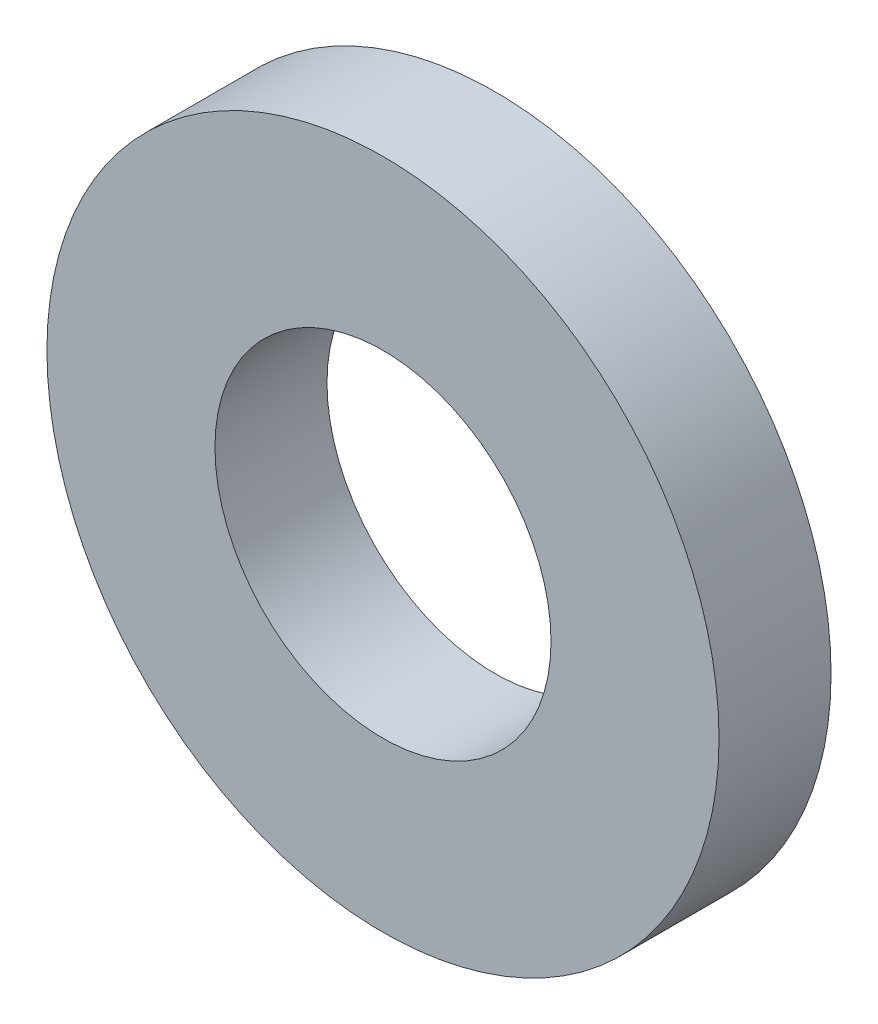
SolidWorks part; units mm, degrees
material "1.0037 (S235JR)"
ref_plane "Front Plane" through (0, 0, 0) normal (0, 0, 1) x (1, 0, 0)
ref_plane "Top Plane" through (0, 0, 0) normal (0, 1, 0) x (1, 0, 0)
ref_plane "Right Plane" through (0, 0, 0) normal (1, 0, 0) x (0, 0, -1)
sketch "Sketch1" plane through (0, 0, 0) normal (0, 0, 1) x (1, 0, 0)
  circle A0 centre (0, 0) radius 15
  circle A1 centre (0, 0) radius 30
  dimension "D1" = 60
  dimension "D2" = 30
extrude "Boss-Extrude1" add sketch "Sketch1" along normal blind 10
